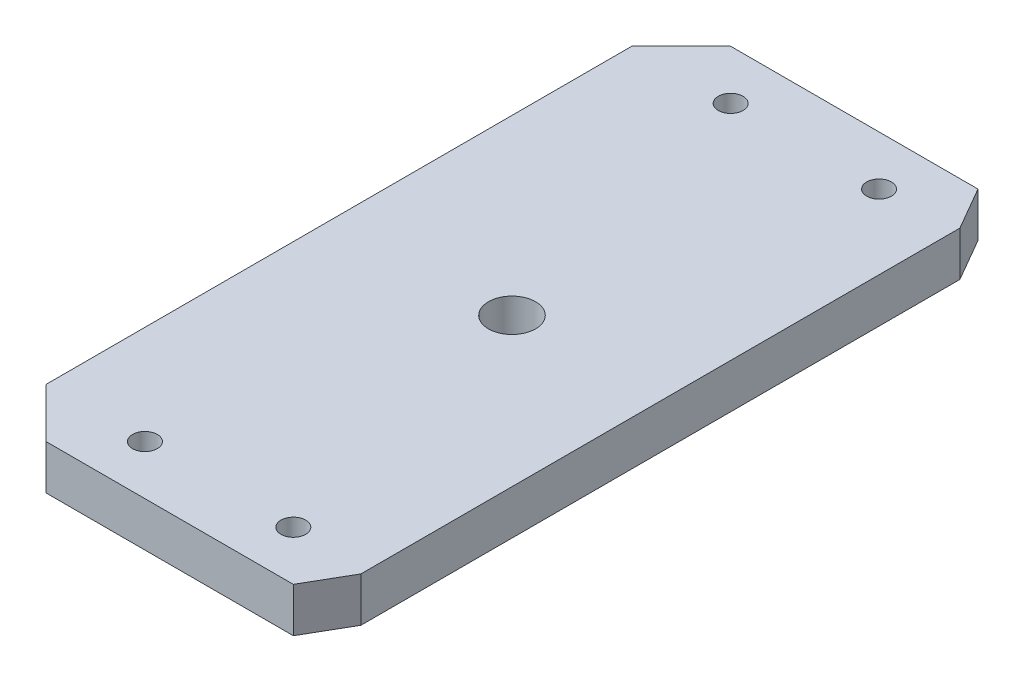
SolidWorks part; units mm, degrees
ref_plane "Alzado" through (0, 0, 0) normal (0, 0, 1) x (1, 0, 0)
ref_plane "Planta" through (0, 0, 0) normal (0, 1, 0) x (1, 0, 0)
ref_plane "Vista lateral" through (0, 0, 0) normal (1, 0, 0) x (0, 0, -1)
sketch "Croquis1" plane through (0, 0, 0) normal (0, 1, 0) x (1, 0, 0)
  line L1 (-25, 69.2) -> (25, 69.2)
  line L2 (-25, 69.2) -> (-25, -69.2)
  line L3 (-25, -69.2) -> (25, -69.2)
  line L4 (25, 69.2) -> (25, -69.2)
  line L5 (-25, 69.2) -> (25, -69.2) construction
  line L6 (-25, -69.2) -> (25, 69.2) construction
  circle A0 centre (0, 0) radius 4.7625
  point P0 (0, 0)
  dimension "D3" = 9.525
  dimension "D1" = 50
  dimension "D2" = 138.4
extrude "Saliente-Extruir1" add sketch "Croquis1" along normal blind 9 contours L2 L1 L4 L3
sketch "Croquis2" plane through (0, 9, 0) normal (0, 1, 0) x (1, 0, 0)
  line L0 (0, 69.2) -> (0, -69.2) construction
  line L1 (25, 69.2) -> (-25, 69.2) construction
  line L2 (-25, -69.2) -> (25, -69.2) construction
  line L3 (-25, -59.2) -> (25, -59.2) construction
  line L4 (-25, 69.2) -> (-25, -69.2) construction
  line L5 (25, -69.2) -> (25, 69.2) construction
  line L6 (0, 0) -> (-25, 0) construction
  circle A0 centre (-15, -59.2) radius 2.5
  circle A1 centre (15, -59.2) radius 2.5
  circle A2 centre (15, 59.2) radius 2.5
  circle A3 centre (-15, 59.2) radius 2.5
  dimension "D3" = 5
  dimension "D1" = 10
  dimension "D2" = 10
extrude "Cortar-Extruir1" cut sketch "Croquis2" against normal through all
sketch "Croquis3" plane through (0, 9, 0) normal (0, 1, 0) x (1, 0, 0)
  line L0 (-25, 69.2) -> (-25, -69.2)
  line L1 (-25, -69.2) -> (-35, -59.2)
  line L2 (-35, -59.2) -> (-35, 59.2)
  line L3 (-35, 0) -> (-25, 0) construction
  line L4 (-25, 69.2) -> (-35, 59.2)
  line L5 (25, 69.2) -> (25, -69.2)
  line L6 (25, -69.2) -> (30, -60.5397)
  line L7 (30, -60.5397) -> (30, 60.5397)
  line L8 (25, 0) -> (30, 0) construction
  line L9 (25, 69.2) -> (30, 60.5397)
  dimension "D1" = 10
  dimension "D2" = 45
  dimension "D3" = 5
  dimension "D4" = 30
extrude "Saliente-Extruir2" add sketch "Croquis3" against normal up to surface (9 mm away) up to face at (-15, 0, -61.7)
